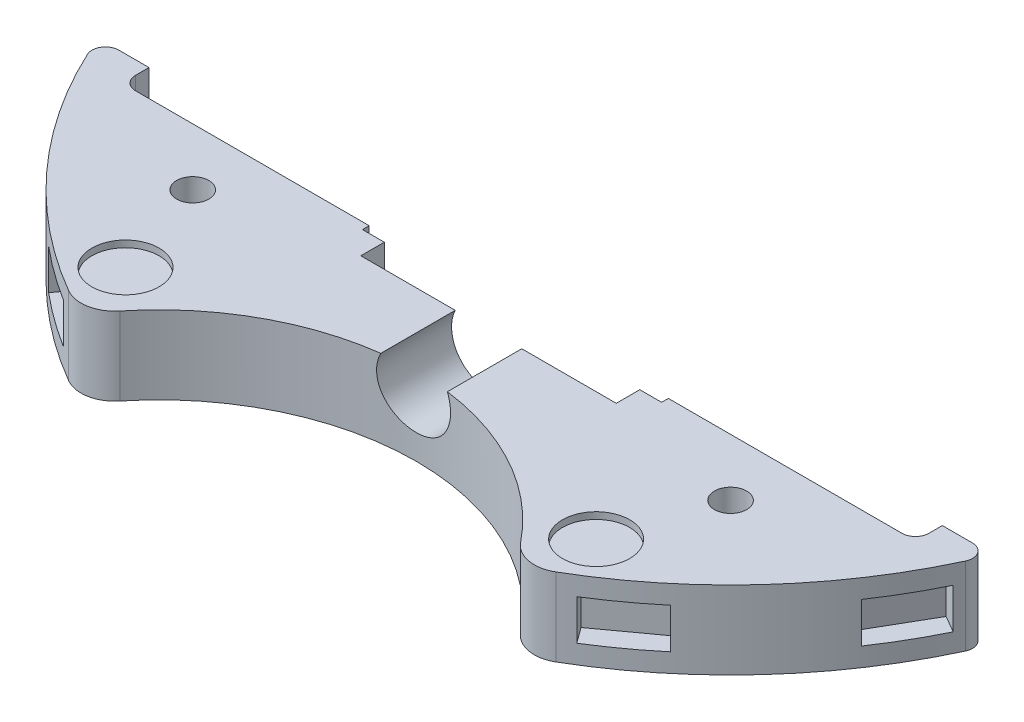
SolidWorks part; units mm, degrees
material "ABS"
ref_plane "Front Plane" through (0, 0, 0) normal (0, 0, 1) x (1, 0, 0)
ref_plane "Top Plane" through (0, 0, 0) normal (0, 1, 0) x (1, 0, 0)
ref_plane "Right Plane" through (0, 0, 0) normal (1, 0, 0) x (0, 0, -1)
sketch "Sketch1" plane through (0, 0, 0) normal (0, 1, 0) x (1, 0, 0)
  line L0 (0, -85) -> (-32.2211, -64.3879) construction
  line L1 (0, -85) -> (0, 0) construction
  arc A0 (36.2245, -62.2237) -> (-36.2245, -62.2237) centre (0, 0) ccw
  arc A1 (29.8119, -61.0352) -> (-29.8119, -61.0352) centre (0, -85) ccw
  arc A2 (36.2245, -62.2237) -> (29.8119, -61.0352) centre (33.7089, -57.9026) cw
  arc A3 (-29.8119, -61.0352) -> (-36.2245, -62.2237) centre (-33.7089, -57.9026) cw
  dimension "D1" = 144
  dimension "D2" = 76.5
  dimension "D4" = 5
  dimension "D3" = 85
extrude "Boss-Extrude1" add sketch "Sketch1" along normal mid plane 11.6
sketch "solenoid placement" plane through (0, 5.8, 0) normal (0, 1, 0) x (1, 0, 0)
  line L0 (0, 0) -> (0, -36) construction
  line L5 (-19, -36) -> (19, -36)
  line L7 (19, -36) -> (19, 28)
  line L9 (19, 28) -> (-19, 28)
  line L11 (-19, 28) -> (-19, -36)
  circle A1 centre (0, 0) radius 72 construction
  arc A2 (36.2245, -62.2237) -> (-36.2245, -62.2237) centre (0, 0) ccw construction
  point P7 (0, 28)
  dimension "D1" = 38
  dimension "D2" = 64
  dimension "D3" = 36
extrude "Cut-Extrude1" cut sketch "solenoid placement" against normal through all
sketch "Sketch6" plane through (0, 5.8, 0) normal (0, 1, 0) x (1, 0, 0)
  line L0 (0, 0) -> (0, -46.75) construction
  arc A0 (29.8119, -61.0352) -> (-29.8119, -61.0352) centre (0, -85) ccw construction
  circle A1 centre (40, -40) radius 2.4
  circle A4 centre (-40, -40) radius 2.4
  dimension "D1" = 4.8
  dimension "D2" = 40
  dimension "D3" = 40
extrude "Cut-Extrude6" cut sketch "Sketch6" against normal through all
sketch "Sketch3" plane through (0, 5.8, 0) normal (0, 1, 0) x (1, 0, 0)
  line L0 (-72, -27.5) -> (-59, -27.5)
  line L1 (-59, -31.5) -> (59, -31.5)
  line L2 (-72, -27.5) -> (-72, 31.5)
  line L3 (-59, -27.5) -> (-59, -31.5)
  line L4 (72, -27.5) -> (72, 31.5)
  line L5 (-72, 31.5) -> (72, 31.5) construction
  line L6 (0, 31.5) -> (0, -31.5) construction
  line L7 (59, -27.5) -> (59, -31.5)
  line L8 (-72, 31.5) -> (-72, 72)
  line L9 (72, -27.5) -> (59, -27.5)
  line L10 (-72, 72) -> (72, 72)
  line L11 (72, 31.5) -> (72, 72)
  arc A0 (36.2245, -62.2237) -> (-36.2245, -62.2237) centre (0, 0) ccw construction
  arc A1 (36.2245, -62.2237) -> (-36.2245, -62.2237) centre (0, 0) ccw construction
  point P0 (0, 0)
  dimension "D2" = 4
  dimension "D1" = 63
  dimension "D3" = 13
extrude "Cut-Extrude3" cut sketch "Sketch3" against normal through all
fillet "Fillet1" radius 2 4 edges at (66.5413, 0, 27.5) (59, 0, 31.5) (-66.5413, 0, 27.5) (-59, 0, 31.5)
sketch "Sketch8" plane through (0, 0, 0) normal (0, 1, 0) x (1, 0, 0)
  line L0 (0, 0) -> (62.3538, -36) construction
  line L1 (0, 0) -> (42.3205, -58.2492) construction
  line L2 (0, 0) -> (14.9696, -70.4266) construction
  line L3 (0, 0) -> (-14.9696, -70.4266) construction
  line L4 (-42.3205, -58.2492) -> (0, 0) construction
  line L5 (0, 0) -> (-62.3538, -36) construction
  line L6 (0, 0) -> (0, -72) construction
  arc A0 (-62.3538, -36) -> (-42.3205, -58.2492) centre (0, 0) ccw construction
  arc A1 (62.3538, -36) -> (42.3205, -58.2492) centre (0, 0) cw construction
  arc A2 (14.9696, -70.4266) -> (42.3205, -58.2492) centre (0, 0) ccw construction
  arc A3 (14.9696, -70.4266) -> (-14.9696, -70.4266) centre (0, 0) cw construction
  arc A4 (-14.9696, -70.4266) -> (-42.3205, -58.2492) centre (0, 0) cw construction
  arc A5 (36.2245, -62.2237) -> (65.294, -30.3429) centre (0, 0) ccw construction
  dimension "D1" = 120
sketch "Sketch9" plane through (0, 0, 0) normal (0, 1, 0) x (1, 0, 0)
  line L0 (0, 0) -> (-59.7033, -40.2432) construction
  line L1 (0, 0) -> (-64.7033, -31.583) construction
  line L2 (-64.7033, -31.583) -> (-59.7033, -40.2432) construction
  line L3 (-64.7033, -31.583) -> (-62.1918, -30.133)
  line L4 (-62.1918, -30.133) -> (-57.1918, -38.7932)
  line L5 (-57.1918, -38.7932) -> (-59.7033, -40.2432)
  line L6 (-46.2635, -55.1697) -> (-44.5589, -52.8235)
  line L7 (-44.5589, -52.8235) -> (-36.4687, -58.7014)
  line L8 (-36.4687, -58.7014) -> (-38.1733, -61.0475)
  line L9 (0, 0) -> (-38.1733, -61.0475) construction
  line L10 (0, 0) -> (-46.2635, -55.1697) construction
  line L11 (-46.2635, -55.1697) -> (-38.1733, -61.0475) construction
  line L12 (-19.8242, -69.217) -> (-19.2213, -66.3804) [skipped]
  line L13 (-19.2213, -66.3804) -> (-9.4398, -68.4595) [skipped]
  line L14 (-9.4398, -68.4595) -> (-10.0428, -71.2962) [skipped]
  line L15 (0, 0) -> (-10.0428, -71.2962) construction
  line L16 (0, 0) -> (-19.8242, -69.217) construction
  line L17 (-19.8242, -69.217) -> (-10.0428, -71.2962) construction
  line L18 (10.0428, -71.2962) -> (9.4398, -68.4595) [skipped]
  line L19 (9.4398, -68.4595) -> (19.2213, -66.3804) [skipped]
  line L20 (19.2213, -66.3804) -> (19.8242, -69.217) [skipped]
  line L21 (0, 0) -> (19.8242, -69.217) construction
  line L22 (0, 0) -> (10.0428, -71.2962) construction
  line L23 (10.0428, -71.2962) -> (19.8242, -69.217) construction
  line L24 (38.1733, -61.0475) -> (36.4687, -58.7014)
  line L25 (36.4687, -58.7014) -> (44.5589, -52.8235)
  line L26 (44.5589, -52.8235) -> (46.2635, -55.1697)
  line L27 (0, 0) -> (46.2635, -55.1697) construction
  line L28 (0, 0) -> (38.1733, -61.0475) construction
  line L29 (38.1733, -61.0475) -> (46.2635, -55.1697) construction
  line L30 (59.7033, -40.2432) -> (57.1918, -38.7932)
  line L31 (57.1918, -38.7932) -> (62.1918, -30.133)
  line L32 (62.1918, -30.133) -> (64.7033, -31.583)
  line L33 (0, 0) -> (64.7033, -31.583) construction
  line L34 (0, 0) -> (59.7033, -40.2432) construction
  line L35 (59.7033, -40.2432) -> (64.7033, -31.583) construction
  arc A0 (-59.7033, -40.2432) -> (-64.7033, -31.583) centre (0, 0) cw
  arc A1 (-62.3538, -36) -> (-42.3205, -58.2492) centre (0, 0) ccw construction
  arc A2 (-38.1733, -61.0475) -> (-46.2635, -55.1697) centre (0, 0) cw
  arc A3 (-10.0428, -71.2962) -> (-19.8242, -69.217) centre (0, 0) cw [skipped]
  arc A4 (19.8242, -69.217) -> (10.0428, -71.2962) centre (0, 0) cw [skipped]
  arc A5 (46.2635, -55.1697) -> (38.1733, -61.0475) centre (0, 0) cw
  arc A6 (64.7033, -31.583) -> (59.7033, -40.2432) centre (0, 0) cw
  point P8 (-62.3538, -36)
  point P12 (62.3538, -36)
  point P34 (0, 0)
  dimension "D1" = 10
  dimension "D2" = 2.9
  dimension "D3" = 6
extrude "Cut-Extrude7" cut sketch "Sketch9" against normal mid plane 6
sketch "Sketch11" plane through (0, 0, 36) normal (0, 0, -1) x (-1, 0, 0)
  line L0 (0, -5.8) -> (0, 3.4) construction
  line L1 (19, -5.8) -> (-19, -5.8) construction
  circle A0 centre (0, 3.4) radius 5.5
  dimension "D2" = 11
  dimension "D1" = 9.2
extrude "Cut-Extrude8" cut sketch "Sketch11" against normal through all
sketch "Sketch12" plane through (0, 5.8, 0) normal (0, 1, 0) x (1, 0, 0)
  line L1 (-22.25, 32.5) -> (22.25, 32.5)
  line L2 (-22.25, 32.5) -> (-22.25, -32.5)
  line L3 (-22.25, -32.5) -> (22.25, -32.5)
  line L4 (22.25, 32.5) -> (22.25, -32.5)
  line L5 (-22.25, 32.5) -> (22.25, -32.5) construction
  line L6 (-22.25, -32.5) -> (22.25, 32.5) construction
  point P0 (0, 0)
  dimension "D1" = 44.5
  dimension "D2" = 65
extrude "Cut-Extrude9" cut sketch "Sketch12" against normal through all
sketch "Sketch13" plane through (0, 5.8, 0) normal (0, 1, 0) x (1, 0, 0)
  line L0 (0, 0) -> (0, -97.3817) construction
  circle A0 centre (-35, -55) radius 5
  circle A1 centre (35, -55) radius 5
  dimension "D3" = 10
  dimension "D1" = 35
  dimension "D2" = 55
extrude "Cut-Extrude10" cut sketch "Sketch13" against normal blind 1
equation "\"smallPulleyTeeth\"= 15"
equation "\"largePulleyTeeth\"= 30"
equation "\"eighthThick\"= 2.9mm"
equation "\"sixteenthThick\" = 1.7mm"
equation "\"quarterThick\"=6.0mm"
equation "\"OD\" = 145mm"
equation "\"puckAngle\" = 60.5deg"
equation "\"puckDiam\" = 76.5mm"
equation "\"D2@Sketch1\"=\"puckDiam\""
equation "\"D1@Boss-Extrude1\"=\"eighthThick\"*4"
equation "\"axlePress\" = 5.9mm"
equation "\"press\" = 0.2mm"
equation "\"wheelClear\" = 0.3mm"
equation "\"10-32clear\" = 4.8mm"
equation "\"6-32clear\" = 3.3mm"
equation "\"8-32clear\" = 4.0mm"
equation "\"wheelHeight\" = 22mm"
equation "\"wheelWell\" = 65mm"
equation "\"puckDist\" = 85mm"
equation "\"scoopFillet\" = 5mm"
equation "\"4-40clear\" = 3.0mm"
equation "\"D3@Sketch1\"=\"puckDist\""
equation "\"D4@Sketch1\"=\"scoopFillet\""
equation "\"D1@Sketch6\"=\"10-32clear\""
equation "\"D2@Sketch9\"=\"eighthThick\""
equation "\"D2@Sketch12\"=\"wheelWell\""
